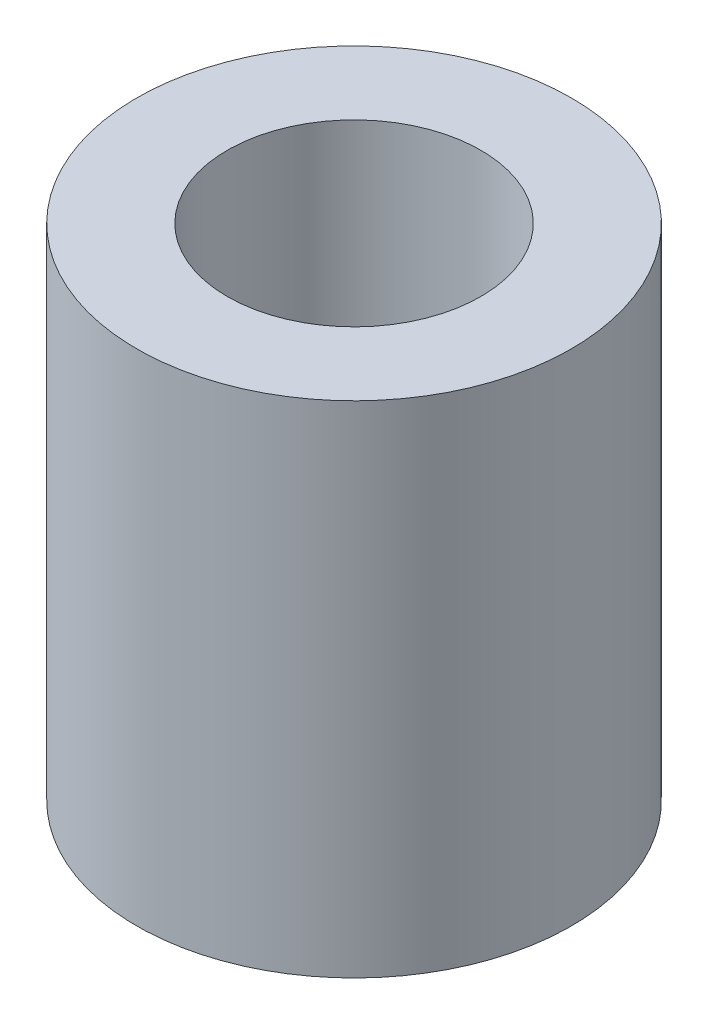
SolidWorks part; units mm, degrees
ref_plane "Front Plane" through (0, 0, 0) normal (0, 0, 1) x (1, 0, 0)
ref_plane "Top Plane" through (0, 0, 0) normal (0, 1, 0) x (1, 0, 0)
ref_plane "Right Plane" through (0, 0, 0) normal (1, 0, 0) x (0, 0, -1)
sketch "Sketch1" plane through (0, 0, 0) normal (0, 1, 0) x (1, 0, 0)
  circle A0 centre (0, 0) radius 3
  dimension "D1" = 6
extrude "Boss-Extrude1" add sketch "Sketch1" along normal blind 6.9
sketch "Sketch2" plane through (0, 6.9, 0) normal (0, 1, 0) x (1, 0, 0)
  circle A0 centre (0, 0) radius 1.75
  circle A1 centre (0, 0) radius 3 construction
  dimension "D1" = 3.5
extrude "Cut-Extrude1" cut sketch "Sketch2" against normal through all
